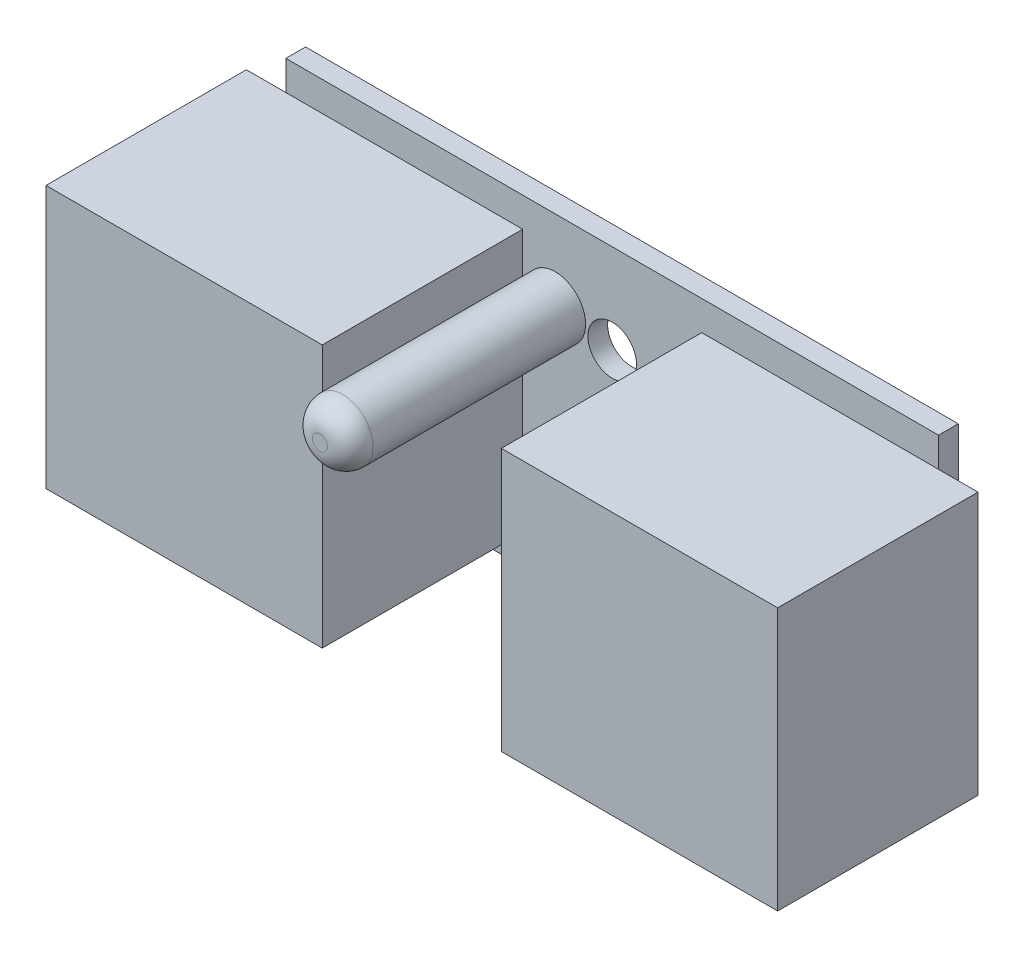
SolidWorks part; units mm, degrees
ref_plane "Płaszczyzna przednia" through (0, 0, 0) normal (0, 0, 1) x (1, 0, 0)
ref_plane "Płaszczyzna górna" through (0, 0, 0) normal (0, 1, 0) x (1, 0, 0)
ref_plane "Płaszczyzna prawa" through (0, 0, 0) normal (1, 0, 0) x (0, 0, -1)
sketch "Sketch1" plane through (0, 0, 0) normal (0, 0, 1) x (1, 0, 0)
  line L1 (0, 0) -> (43, 0)
  line L2 (0, 0) -> (0, 21.2)
  line L3 (0, 21.2) -> (43, 21.2)
  line L4 (43, 0) -> (43, 21.2)
  circle A0 centre (21.5, 15.3) radius 1.6
  dimension "D3" = 21.5
  dimension "D5" = 3.2
  dimension "D1" = 21.2
  dimension "D2" = 43
  dimension "D4" = 5.9
extrude "Boss-Extrude1" add sketch "Sketch1" along normal blind 1.3
sketch "Sketch2" plane through (0, 0, 1.3) normal (0, 0, 1) x (1, 0, 0)
  line L0 (43, 21.2) -> (0, 21.2) construction
  line L1 (0, 21.2) -> (0, 0) construction
  circle A0 centre (17.75, 15.9) radius 2
  dimension "D1" = 4
  dimension "D2" = 5.3
  dimension "D3" = 17.75
extrude "Boss-Extrude2" add sketch "Sketch2" along normal blind 15.5
fillet "Fillet1" radius 1.5 1 edges at (19.75, 15.9, 16.8)
sketch "Sketch3" plane through (0, 0, 1.3) normal (0, 0, 1) x (1, 0, 0)
  line L1 (45.6, 1.95) -> (27.4, 1.95)
  line L2 (45.6, 1.95) -> (45.6, 19.25)
  line L3 (45.6, 19.25) -> (27.4, 19.25)
  line L4 (27.4, 1.95) -> (27.4, 19.25)
  line L5 (43, 10.6) -> (0, 10.6) construction
  line L6 (-2.6, 19.25) -> (15.6, 19.25)
  line L7 (-2.6, 19.25) -> (-2.6, 1.95)
  line L8 (-2.6, 1.95) -> (15.6, 1.95)
  line L9 (15.6, 19.25) -> (15.6, 1.95)
  line L10 (43, 0) -> (43, 21.2) construction
  line L11 (0, 21.2) -> (0, 0) construction
  line L12 (31.2205, 19.25) -> (31.2205, 10.6) construction
  line L13 (31.2205, 10.6) -> (31.2205, 1.95) construction
  line L14 (45.6, 14.3473) -> (43, 14.3473) construction
  line L15 (0, 15.3434) -> (-2.6, 15.3434) construction
  dimension "D1" = 17.3
  dimension "D2" = 18.2
  dimension "D3" = 17.3
  dimension "D4" = 18.2
  dimension "D5" = 48.2
extrude "Boss-Extrude3" add sketch "Sketch3" along normal blind 13.2
